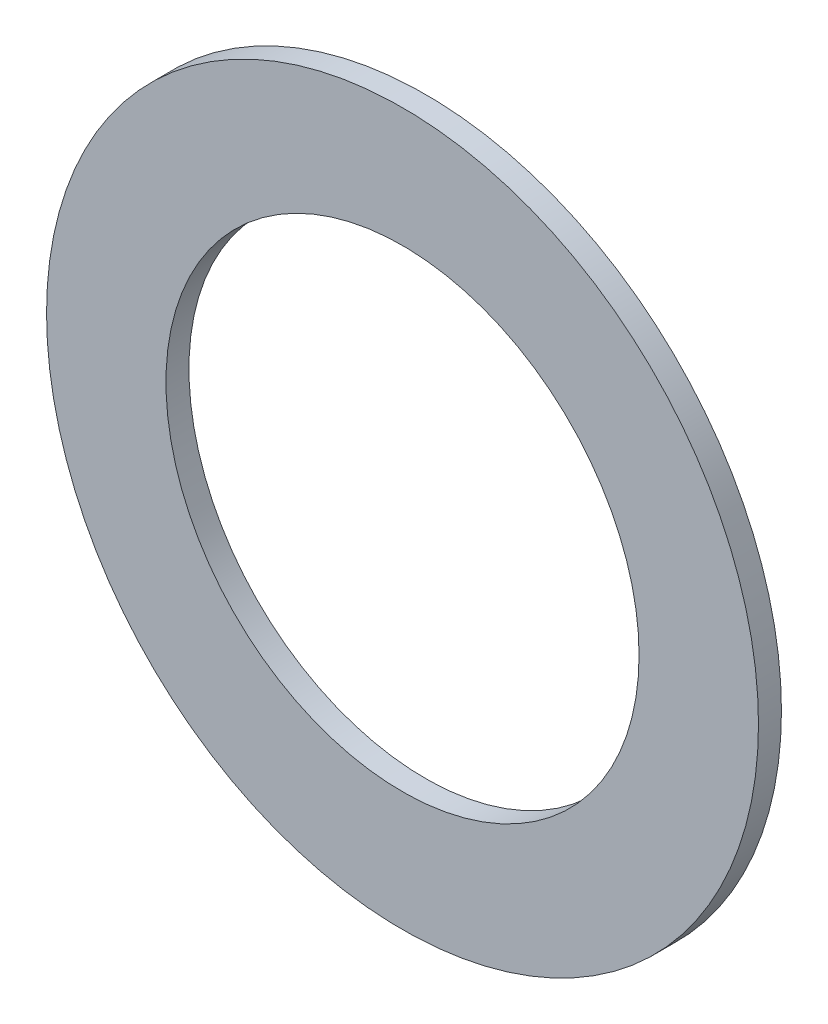
SolidWorks part; units mm, degrees
material "Plain Carbon Steel"
ref_plane "Front Plane" through (0, 0, 0) normal (0, 0, 1) x (1, 0, 0)
ref_plane "Top Plane" through (0, 0, 0) normal (0, 1, 0) x (1, 0, 0)
ref_plane "Right Plane" through (0, 0, 0) normal (1, 0, 0) x (0, 0, -1)
sketch "Sketch1" plane through (0, 0, 0) normal (1, 0, 0) x (0, 0, -1)
  line L0 (-5.2206, 0) -> (9.1636, 0) construction
  line L1 (0, 2.6162) -> (0.254, 2.6162)
  line L2 (0, 2.6162) -> (0, 3.937)
  line L3 (0.254, 2.6162) -> (0.254, 3.937)
  line L4 (0, 3.937) -> (0.254, 3.937)
  dimension "D1" = 5.2324
  dimension "D2" = 7.874
  dimension "D3" = 0.254
revolve "Revolve1" add sketch "Sketch1" angle 360 about L0
